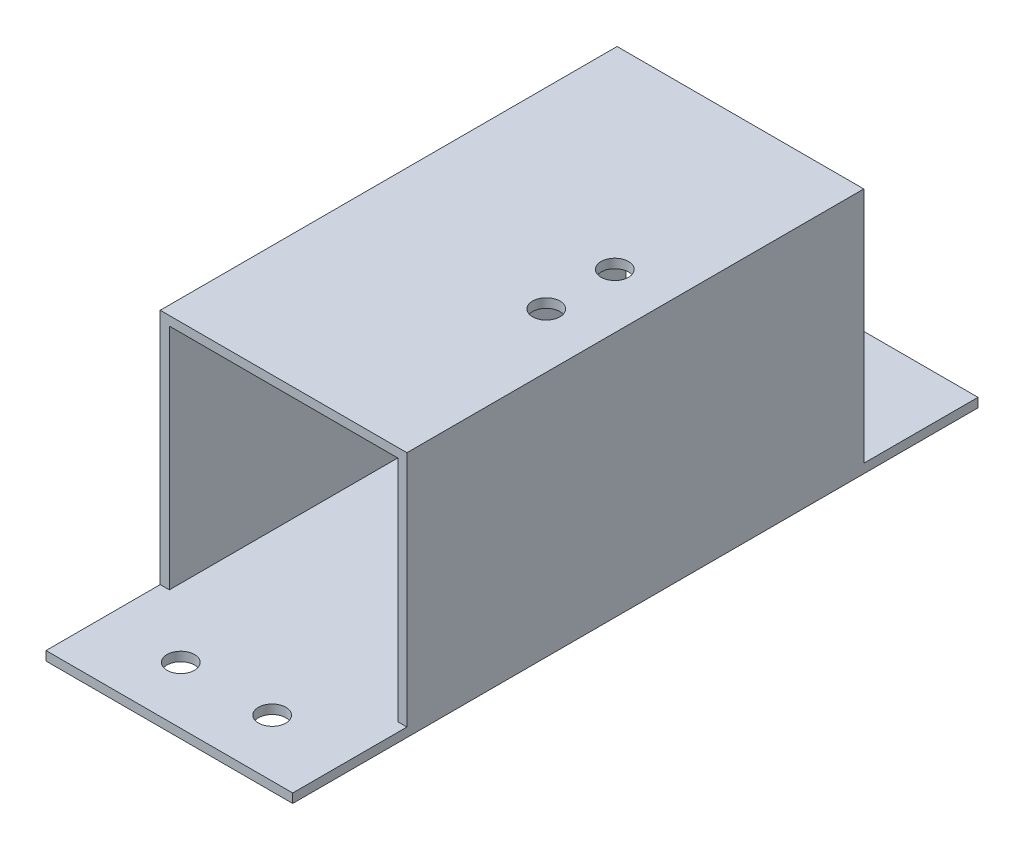
SolidWorks part; units mm, degrees
material "Plain Carbon Steel"
ref_plane "Front Plane" through (0, 0, 0) normal (0, 0, 1) x (1, 0, 0)
ref_plane "Top Plane" through (0, 0, 0) normal (0, 1, 0) x (1, 0, 0)
ref_plane "Right Plane" through (0, 0, 0) normal (1, 0, 0) x (0, 0, -1)
sketch "Sketch1" plane through (0, 0, 0) normal (0, 0, 1) x (1, 0, 0)
  line L1 (27, -27) -> (-27, -27)
  line L2 (27, -27) -> (27, 27)
  line L3 (27, 27) -> (-27, 27)
  line L4 (-27, -27) -> (-27, 27)
  line L5 (27, -27) -> (-27, 27) construction
  line L6 (27, 27) -> (-27, -27) construction
  line L7 (25, -25) -> (-25, -25)
  line L8 (25, -25) -> (25, 25)
  line L9 (25, 25) -> (-25, 25)
  line L10 (-25, -25) -> (-25, 25)
  line L11 (25, -25) -> (-25, 25) construction
  line L12 (25, 25) -> (-25, -25) construction
  point P0 (0, 0)
  point P6 (0, 0)
  dimension "D1" = 54
  dimension "D2" = 50
  dimension "D3" = 54
  dimension "D4" = 50
extrude "Boss-Extrude1" add sketch "Sketch1" along normal mid plane 100
sketch "Sketch2" plane through (0, 0, 50) normal (0, 0, 1) x (1, 0, 0)
  line L0 (27, -27) -> (27, 27) construction
  line L1 (-27, -27) -> (27, -27)
  line L2 (-27, -27) -> (-27, -25)
  line L3 (-27, -25) -> (27, -25)
  line L4 (27, -27) -> (27, -25)
  dimension "D1" = 2
extrude "Boss-Extrude2" add sketch "Sketch2" along normal blind 25 and the other way blind 125
sketch "Sketch3" plane through (0, -25, 0) normal (0, 1, 0) x (1, 0, 0)
  line L0 (-1000, 0) -> (49000, 0) construction
  circle A0 centre (-10, -62.5) radius 3
  circle A1 centre (10, -62.5) radius 3
  circle A2 centre (10, 62.5) radius 3
  circle A3 centre (-10, 62.5) radius 3
  dimension "D1" = 20
  dimension "D2" = 6
  dimension "D3" = 6
  dimension "D4" = 62.5
  dimension "D5" = 10
  dimension "D6" = 10
extrude "Cut-Extrude1" cut sketch "Sketch3" against normal blind 25
sketch "Sketch4" plane through (0, 27, 0) normal (0, 1, 0) x (1, 0, 0)
  circle A0 centre (15, 7.5) radius 3
  circle A1 centre (15, -7.5) radius 3
  dimension "D1" = 6
  dimension "D2" = 6
  dimension "D3" = 7.5
  dimension "D4" = 7.5
  dimension "D5" = 15
  dimension "D6" = 15
extrude "Cut-Extrude2" cut sketch "Sketch4" against normal blind 25
